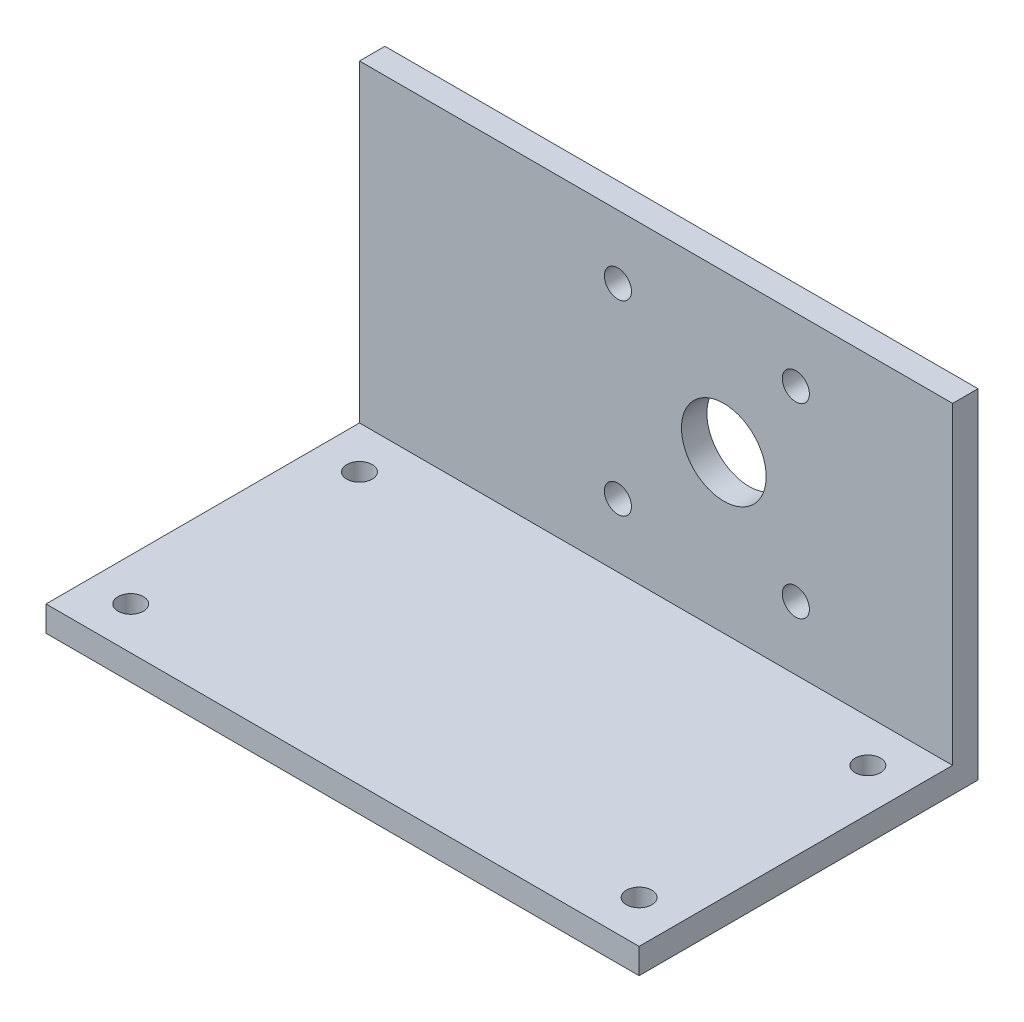
SolidWorks part; units mm, degrees
ref_plane "Спереди" through (0, 0, 0) normal (0, 0, 1) x (1, 0, 0)
ref_plane "Сверху" through (0, 0, 0) normal (0, 1, 0) x (1, 0, 0)
ref_plane "Справа" through (0, 0, 0) normal (1, 0, 0) x (0, 0, -1)
sketch "Эскиз1" plane through (0, 0, 0) normal (1, 0, 0) x (0, 0, -1)
  line L0 (17, -17) -> (-20, -17)
  line L1 (17, 20) -> (20, 20)
  line L2 (17, 20) -> (17, -17)
  line L3 (20, 20) -> (-20, -20) construction
  line L10 (20, 20) -> (20, -20)
  line L11 (-20, -17) -> (-20, -20)
  line L12 (-20, -20) -> (20, -20)
  point P0 (0, 0)
  point P1 (0, 0)
  dimension "D1" = 40
  dimension "D2" = 3
extrude "Бобышка-Вытянуть1" add sketch "Эскиз1" along normal blind 70
sketch "Эскиз2" plane through (0, 0, -17) normal (0, 0, 1) x (1, 0, 0)
  circle A0 centre (43, 1.5) radius 5
  arc A3 (40.7639, 3.5) -> (45.2361, 3.5) centre (43, 1.5) ccw construction
  circle A4 centre (51.5, 12.5) radius 1.6
  circle A5 centre (30.5, 12.5) radius 1.6
  circle A6 centre (30.5, -9.5) radius 1.6
  circle A7 centre (51.5, -9.5) radius 1.6
  circle A8 centre (51.5, 12.5) radius 1.5 construction
  circle A9 centre (30.5, 12.5) radius 1.5 construction
  circle A10 centre (30.5, -9.5) radius 1.5 construction
  circle A11 centre (51.5, -9.5) radius 1.5 construction
  dimension "D1" = 10
  dimension "D2" = 3.2
extrude "Вырез-Вытянуть1" cut sketch "Эскиз2" against normal up to surface (3 mm away) up to face at (35, 0, -20)
sketch "Эскиз3" plane through (0, -17, 0) normal (0, 1, 0) x (1, 0, 0)
  line L0 (0, -1.5) -> (70, -1.5) construction
  line L1 (0, 17) -> (0, -20) construction
  line L2 (70, 17) -> (70, -20) construction
  line L3 (65, -1.5) -> (65, -15) construction
  line L4 (35, -20) -> (35, -1.5) construction
  line L5 (70, -20) -> (0, -20) construction
  circle A0 centre (65, -15) radius 1.5
  circle A1 centre (65, 12) radius 1.5
  circle A2 centre (5, -15) radius 1.5
  circle A3 centre (5, 12) radius 1.5
  dimension "D1" = 3
  dimension "D2" = 5
  dimension "D3" = 5
extrude "Вырез-Вытянуть2" cut sketch "Эскиз3" against normal up to surface (3 mm away) up to face at (35, -20, 0)
